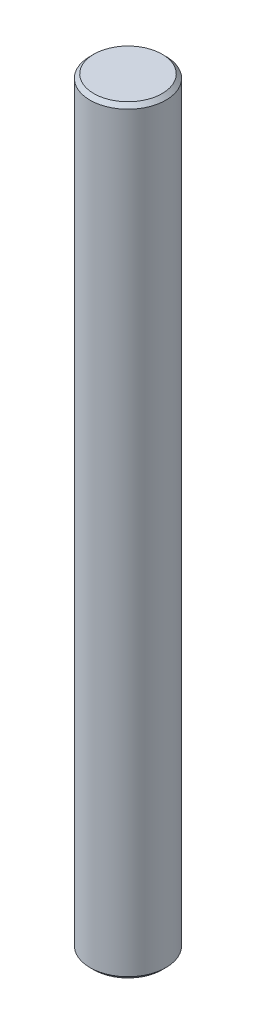
SolidWorks part; units mm, degrees
material "AISI 1045 Steel, cold drawn"
ref_plane "Front Plane" through (0, 0, 0) normal (0, 0, 1) x (1, 0, 0)
ref_plane "Top Plane" through (0, 0, 0) normal (0, 1, 0) x (1, 0, 0)
ref_plane "Right Plane" through (0, 0, 0) normal (1, 0, 0) x (0, 0, -1)
sketch "Sketch1" plane through (0, 0, 0) normal (0, 1, 0) x (1, 0, 0)
  circle A0 centre (0, 0) radius 2.5
  dimension "D1" = 5
extrude "Boss-Extrude1" add sketch "Sketch1" along normal mid plane 50
chamfer "Chamfer1" distance 0.25 angle 45 2 edges at (0, -25, 2.5) (0, 25, 2.5)
